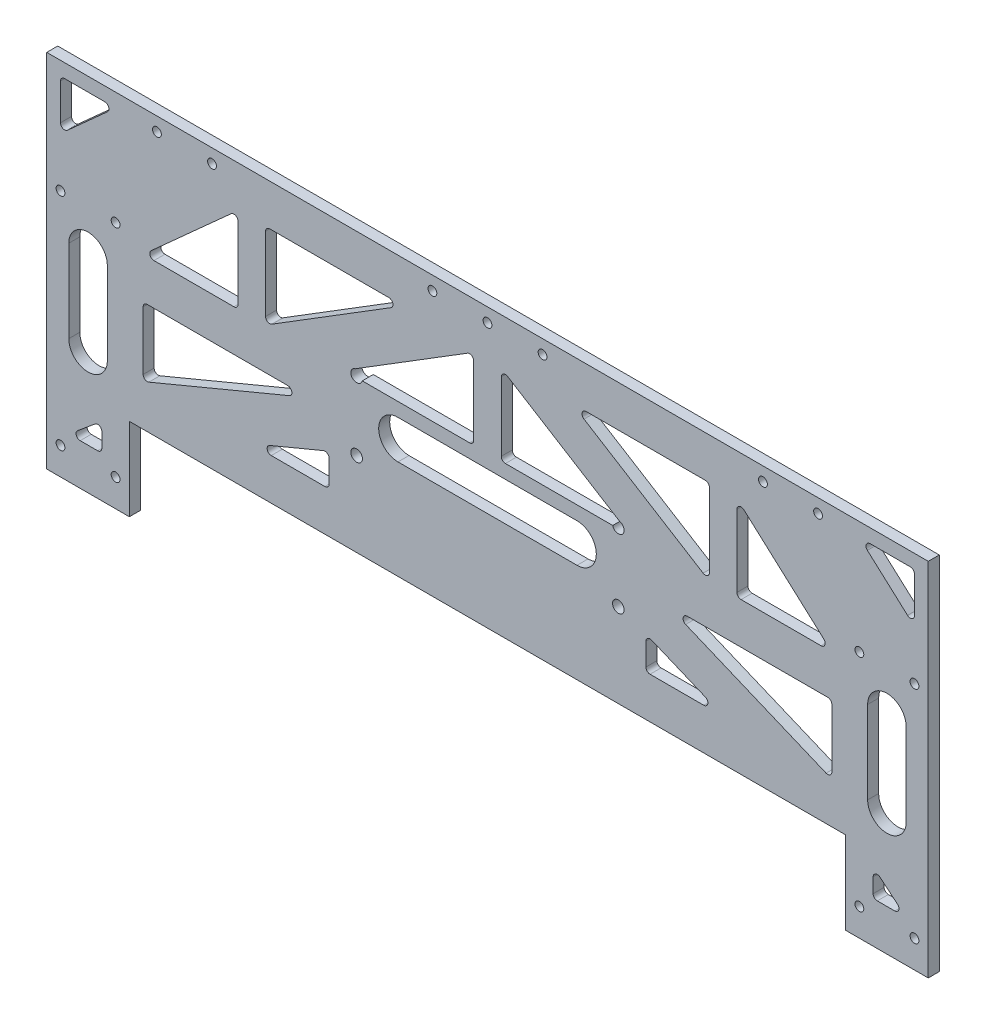
SolidWorks part; units mm, degrees
material "Thornel Mat VMA"
ref_plane "前视基准面" through (0, 0, 0) normal (0, 0, 1) x (1, 0, 0)
ref_plane "上视基准面" through (0, 0, 0) normal (0, 1, 0) x (1, 0, 0)
ref_plane "右视基准面" through (0, 0, 0) normal (1, 0, 0) x (0, 0, -1)
sketch "草图1" plane through (0, 0, 0) normal (0, 0, 1) x (1, 0, 0)
  line L1 (0, 0) -> (320, 0)
  line L2 (0, 0) -> (0, 131)
  line L3 (0, 131) -> (320, 131)
  line L4 (320, 0) -> (320, 131)
  dimension "D1" = 320
  dimension "D2" = 131
extrude "凸台-拉伸1" add sketch "草图1" along normal blind 4
sketch "草图2" plane through (0, 0, 4) normal (0, 0, 1) x (1, 0, 0)
  line L0 (160, 131) -> (160, 0) construction
  line L1 (320, 131) -> (0, 131) construction
  line L2 (0, 0) -> (320, 0) construction
  line L3 (0, 131) -> (0, 0) construction
  line L4 (30, 0) -> (35, 0)
  line L5 (30, 0) -> (30, 30)
  line L6 (30, 30) -> (35, 30)
  line L7 (35, 0) -> (35, 30)
  line L8 (285, 0) -> (285, 30)
  line L9 (290, 30) -> (285, 30)
  line L10 (290, 0) -> (290, 30)
  line L11 (290, 0) -> (285, 0)
  dimension "D1" = 30
  dimension "D2" = 30
  dimension "D3" = 5
extrude "切除-拉伸1" cut sketch "草图2" against normal through all
sketch "草图3" plane through (0, 0, 4) normal (0, 0, 1) x (1, 0, 0)
  line L0 (40, 126) -> (60, 126) construction
  line L1 (160, 131) -> (160, 0) construction
  line L2 (320, 131) -> (0, 131) construction
  line L3 (35, 0) -> (285, 0) construction
  line L4 (140, 126) -> (160, 126) construction
  line L5 (0, 131) -> (0, 0) construction
  line L6 (280, 126) -> (260, 126) construction
  circle A0 centre (40, 126) radius 1.6
  circle A1 centre (60, 126) radius 1.6
  circle A2 centre (140, 126) radius 1.6
  circle A3 centre (160, 126) radius 1.6
  circle A4 centre (260, 126) radius 1.6
  circle A5 centre (280, 126) radius 1.6
  circle A6 centre (180, 126) radius 1.6
  dimension "D5" = 3.2
  dimension "D1" = 40
  dimension "D2" = 5
  dimension "D3" = 20
  dimension "D4" = 20
extrude "切除-拉伸2" cut sketch "草图3" against normal through all
sketch "草图4" plane through (0, 0, 4) normal (0, 0, 1) x (1, 0, 0)
  line L0 (160, 131) -> (160, 0) construction
  line L1 (5, 90) -> (25, 90) construction
  line L2 (5, 90) -> (5, 10) construction
  line L3 (5, 10) -> (25, 10) construction
  line L4 (25, 90) -> (25, 10) construction
  line L5 (320, 131) -> (0, 131) construction
  line L6 (35, 0) -> (285, 0) construction
  line L7 (0, 0) -> (30, 0) construction
  line L8 (0, 131) -> (0, 0) construction
  line L10 (295, 90) -> (295, 10) construction
  line L11 (315, 10) -> (295, 10) construction
  line L12 (315, 90) -> (315, 10) construction
  line L13 (315, 90) -> (295, 90) construction
  circle A0 centre (5, 90) radius 1.6
  circle A1 centre (25, 90) radius 1.6
  circle A2 centre (5, 10) radius 1.6
  circle A3 centre (25, 10) radius 1.6
  circle A4 centre (295, 10) radius 1.6
  circle A5 centre (315, 10) radius 1.6
  circle A6 centre (295, 90) radius 1.6
  circle A7 centre (315, 90) radius 1.6
  dimension "D5" = 3.2
  dimension "D1" = 10
  dimension "D2" = 80
  dimension "D3" = 5
  dimension "D4" = 20
extrude "切除-拉伸3" cut sketch "草图4" against normal through all
sketch "草图6" plane through (0, 0, 4) normal (0, 0, 1) x (1, 0, 0)
  line L0 (160, 131) -> (160, 0) construction
  line L1 (320, 131) -> (0, 131) construction
  line L2 (35, 0) -> (285, 0) construction
  line L3 (127.5, 73) -> (192.5, 73) construction
  line L4 (112.5, 60.5) -> (207.5, 60.5) construction
  line L5 (112.5, 60.5) -> (112.5, 85.5) construction
  line L6 (112.5, 85.5) -> (207.5, 85.5) construction
  line L7 (207.5, 60.5) -> (207.5, 85.5) construction
  line L8 (112.5, 60.5) -> (207.5, 85.5) construction
  line L9 (112.5, 85.5) -> (207.5, 60.5) construction
  line L10 (127.5, 80) -> (192.5, 80)
  line L11 (127.5, 66) -> (192.5, 66)
  circle A0 centre (112.5, 85.5) radius 2.1
  circle A1 centre (207.5, 85.5) radius 2.1
  circle A2 centre (207.5, 60.5) radius 2.1
  circle A3 centre (112.5, 60.5) radius 2.1
  arc A4 (127.5, 80) -> (127.5, 66) centre (127.5, 73) ccw
  arc A5 (192.5, 66) -> (192.5, 80) centre (192.5, 73) ccw
  point P6 (160, 73)
  point P17 (160, 73)
  dimension "D1" = 4.2
  dimension "D5" = 7
  dimension "D2" = 25
  dimension "D3" = 95
  dimension "D4" = 45.5
  dimension "D6" = 15
extrude "切除-拉伸5" cut sketch "草图6" against normal through all
sketch "草图5" plane through (0, 0, 4) normal (0, 0, 1) x (1, 0, 0)
  line L0 (5, 111.368) -> (5, 124.5)
  line L1 (6.5, 126) -> (21.0911, 126)
  line L2 (22.0945, 123.3851) -> (7.5034, 110.2531)
  line L3 (15, 75) -> (15, 45) construction
  line L4 (22, 75) -> (22, 45)
  line L5 (8, 75) -> (8, 45)
  line L6 (5, 90) -> (25, 90) construction
  line L7 (0, 131) -> (0, 0) construction
  line L8 (320, 131) -> (0, 131) construction
  line L9 (38.9089, 85) -> (67.9444, 85)
  line L10 (69.4444, 86.5) -> (69.4444, 112.632)
  line L11 (66.941, 113.7469) -> (37.9055, 87.6149)
  line L12 (160, 131) -> (160, 0) construction
  line L13 (35, 0) -> (285, 0) construction
  line L14 (35, 68.5) -> (35, 47.25)
  line L15 (35, 0) -> (285, 0)
  line L16 (35, 0) -> (35, 30)
  line L17 (35, 30) -> (285, 30)
  line L18 (285, 0) -> (285, 30)
  line L19 (37.0769, 45.8654) -> (88.0769, 67.1154)
  line L20 (87.5, 70) -> (36.5, 70)
  line L21 (81.5, 45) -> (101, 45)
  line L22 (102.5, 46.5) -> (102.5, 54.625)
  line L23 (100.4231, 56.0096) -> (80.9231, 47.8846)
  line L24 (79.4444, 87.6949) -> (79.4444, 114.5)
  line L25 (80.9444, 116) -> (124.1785, 116)
  line L26 (124.9689, 113.2251) -> (81.7349, 86.4201)
  line L27 (113.1767, 85) -> (153.5, 85)
  line L28 (155, 86.5) -> (155, 111.5005)
  line L29 (152.7096, 112.7753) -> (112.3863, 87.7749)
  line L30 (315, 90) -> (295, 90) construction
  line L31 (167.2904, 112.7753) -> (207.6137, 87.7749)
  line L32 (165, 86.5) -> (165, 111.5005)
  line L33 (206.8233, 85) -> (166.5, 85)
  line L34 (195.0311, 113.2251) -> (238.2651, 86.4201)
  line L35 (239.0556, 116) -> (195.8215, 116)
  line L36 (240.5556, 87.6949) -> (240.5556, 114.5)
  line L37 (219.5769, 56.0096) -> (239.0769, 47.8846)
  line L38 (217.5, 46.5) -> (217.5, 54.625)
  line L39 (238.5, 45) -> (219, 45)
  line L40 (232.5, 70) -> (283.5, 70)
  line L41 (282.9231, 45.8654) -> (231.9231, 67.1154)
  line L42 (285, 68.5) -> (285, 47.25)
  line L43 (253.059, 113.7469) -> (282.0945, 87.6149)
  line L44 (250.5556, 86.5) -> (250.5556, 112.632)
  line L45 (281.0911, 85) -> (252.0556, 85)
  line L46 (297.9055, 123.3851) -> (312.4966, 110.2531)
  line L47 (313.5, 126) -> (298.9089, 126)
  line L48 (315, 111.368) -> (315, 124.5)
  line L49 (305, 75) -> (305, 45) construction
  line L50 (298, 75) -> (298, 45)
  line L51 (312, 75) -> (312, 45)
  line L52 (192.5, 80) -> (127.5, 80) construction
  line L53 (12.1431, 15) -> (18.5, 15)
  line L54 (20, 16.5) -> (20, 21.7974)
  line L55 (17.5397, 22.9498) -> (11.1828, 17.6523)
  line L56 (30, 30) -> (30, 0) construction
  line L57 (302.4603, 22.9498) -> (308.8172, 17.6523)
  line L58 (300, 16.5) -> (300, 21.7974)
  line L59 (307.8569, 15) -> (301.5, 15)
  arc A0 (22, 75) -> (8, 75) centre (15, 75) ccw
  arc A1 (8, 45) -> (22, 45) centre (15, 45) ccw
  arc A2 (155, 111.5005) -> (152.7096, 112.7753) centre (153.5, 111.5005) ccw
  circle A3 centre (5, 10) radius 1.6 construction
  arc A4 (21.0911, 126) -> (22.0945, 123.3851) centre (21.0911, 124.5) cw
  arc A5 (5, 111.368) -> (7.5034, 110.2531) centre (6.5, 111.368) ccw
  arc A6 (5, 124.5) -> (6.5, 126) centre (6.5, 124.5) cw
  arc A7 (67.9444, 85) -> (69.4444, 86.5) centre (67.9444, 86.5) ccw
  arc A8 (38.9089, 85) -> (37.9055, 87.6149) centre (38.9089, 86.5) cw
  arc A9 (69.4444, 112.632) -> (66.941, 113.7469) centre (67.9444, 112.632) ccw
  arc A10 (88.0769, 67.1154) -> (87.5, 70) centre (87.5, 68.5) ccw
  arc A11 (35, 47.25) -> (37.0769, 45.8654) centre (36.5, 47.25) ccw
  arc A12 (35, 68.5) -> (36.5, 70) centre (36.5, 68.5) cw
  circle A13 centre (112.5, 85.5) radius 2.1 construction
  arc A14 (101, 45) -> (102.5, 46.5) centre (101, 46.5) ccw
  arc A15 (81.5, 45) -> (80.9231, 47.8846) centre (81.5, 46.5) cw
  arc A16 (102.5, 54.625) -> (100.4231, 56.0096) centre (101, 54.625) ccw
  arc A17 (153.5, 85) -> (155, 86.5) centre (153.5, 86.5) ccw
  arc A18 (113.1767, 85) -> (112.3863, 87.7749) centre (113.1767, 86.5) cw
  arc A19 (79.4444, 87.6949) -> (81.7349, 86.4201) centre (80.9444, 87.6949) ccw
  arc A20 (79.4444, 114.5) -> (80.9444, 116) centre (80.9444, 114.5) cw
  arc A21 (124.1785, 116) -> (124.9689, 113.2251) centre (124.1785, 114.5) cw
  arc A22 (195.8215, 116) -> (195.0311, 113.2251) centre (195.8215, 114.5) ccw
  arc A23 (240.5556, 114.5) -> (239.0556, 116) centre (239.0556, 114.5) ccw
  arc A24 (240.5556, 87.6949) -> (238.2651, 86.4201) centre (239.0556, 87.6949) cw
  arc A25 (206.8233, 85) -> (207.6137, 87.7749) centre (206.8233, 86.5) ccw
  arc A26 (166.5, 85) -> (165, 86.5) centre (166.5, 86.5) cw
  arc A27 (217.5, 54.625) -> (219.5769, 56.0096) centre (219, 54.625) cw
  arc A28 (238.5, 45) -> (239.0769, 47.8846) centre (238.5, 46.5) ccw
  arc A29 (219, 45) -> (217.5, 46.5) centre (219, 46.5) cw
  arc A30 (285, 68.5) -> (283.5, 70) centre (283.5, 68.5) ccw
  arc A31 (285, 47.25) -> (282.9231, 45.8654) centre (283.5, 47.25) cw
  arc A32 (231.9231, 67.1154) -> (232.5, 70) centre (232.5, 68.5) cw
  arc A33 (250.5556, 112.632) -> (253.059, 113.7469) centre (252.0556, 112.632) cw
  arc A34 (281.0911, 85) -> (282.0945, 87.6149) centre (281.0911, 86.5) ccw
  arc A35 (252.0556, 85) -> (250.5556, 86.5) centre (252.0556, 86.5) cw
  arc A36 (315, 124.5) -> (313.5, 126) centre (313.5, 124.5) ccw
  arc A37 (315, 111.368) -> (312.4966, 110.2531) centre (313.5, 111.368) cw
  arc A38 (298.9089, 126) -> (297.9055, 123.3851) centre (298.9089, 124.5) ccw
  arc A39 (165, 111.5005) -> (167.2904, 112.7753) centre (166.5, 111.5005) cw
  arc A40 (298, 75) -> (312, 75) centre (305, 75) cw
  arc A41 (312, 45) -> (298, 45) centre (305, 45) cw
  arc A42 (18.5, 15) -> (20, 16.5) centre (18.5, 16.5) ccw
  arc A43 (12.1431, 15) -> (11.1828, 17.6523) centre (12.1431, 16.5) cw
  arc A44 (20, 21.7974) -> (17.5397, 22.9498) centre (18.5, 21.7974) ccw
  arc A45 (300, 21.7974) -> (302.4603, 22.9498) centre (301.5, 21.7974) cw
  arc A46 (307.8569, 15) -> (308.8172, 17.6523) centre (307.8569, 16.5) ccw
  arc A47 (301.5, 15) -> (300, 16.5) centre (301.5, 16.5) cw
  point P5 (15, 60)
  point P12 (15, 90)
  point P23 (25, 126)
  point P26 (5, 108)
  point P29 (5, 126)
  point P40 (35, 85)
  point P43 (69.4444, 116)
  point P56 (95, 70)
  point P59 (35, 45)
  point P62 (35, 70)
  point P84 (155, 114.1954)
  point P87 (155, 85)
  point P90 (107.9107, 85)
  point P93 (79.4444, 85)
  point P96 (79.4444, 116)
  point P99 (129.4444, 116)
  point P156 (190.5556, 116)
  point P157 (240.5556, 116)
  point P158 (240.5556, 85)
  point P159 (212.0893, 85)
  point P160 (165, 85)
  point P161 (165, 114.1954)
  point P162 (285, 70)
  point P163 (285, 45)
  point P164 (225, 70)
  point P165 (250.5556, 116)
  point P166 (285, 85)
  point P167 (315, 126)
  point P168 (315, 108)
  point P169 (295, 126)
  point P172 (305, 60)
  point P186 (20, 15)
  point P189 (8, 15)
  point P192 (20, 25)
  point P202 (300, 25)
  point P203 (312, 15)
  point P204 (300, 15)
  dimension "D1" = 7
  dimension "D8" = 1.5
  dimension "D12" = 1.5
  dimension "D16" = 1.5
  dimension "D20" = 1.5
  dimension "D27" = 1.5
  dimension "D32" = 1.5
  dimension "D2" = 15
  dimension "D3" = 35
  dimension "D4" = 5
  dimension "D5" = 5
  dimension "D6" = 20
  dimension "D7" = 18
  dimension "D9" = 5
  dimension "D10" = 10
  dimension "D11" = 10
  dimension "D13" = 15
  dimension "D14" = 15
  dimension "D15" = 60
  dimension "D17" = 15
  dimension "D18" = 10
  dimension "D19" = 15
  dimension "D21" = 15
  dimension "D22" = 10
  dimension "D23" = 50
  dimension "D24" = 15
  dimension "D25" = 10
  dimension "D26" = 5
  dimension "D28" = 10
  dimension "D29" = 8
  dimension "D30" = 5
  dimension "D31" = 10
extrude "切除-拉伸4" cut sketch "草图5" against normal through all
